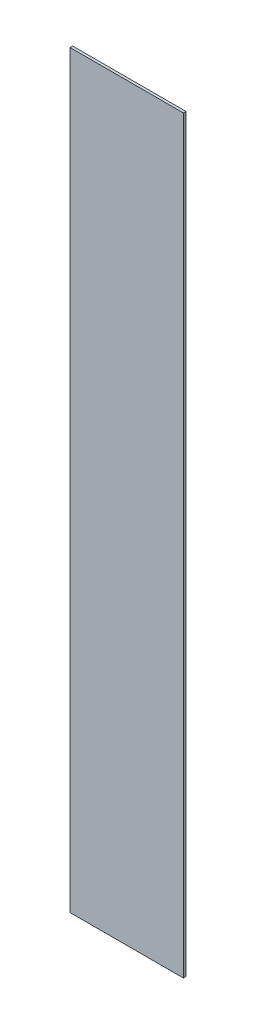
SolidWorks part; units mm, degrees
material "Chapa F.F 1020 - 1,5 mm"
ref_plane "Plano frontal" through (0, 0, 0) normal (0, 0, 1) x (1, 0, 0)
ref_plane "Plano superior" through (0, 0, 0) normal (0, 1, 0) x (1, 0, 0)
ref_plane "Plano direito" through (0, 0, 0) normal (1, 0, 0) x (0, 0, -1)
sketch "Esboço1" plane through (0, 0, 0) normal (0, 0, 1) x (1, 0, 0)
  line L1 (0, 0) -> (65, 0)
  line L2 (0, 0) -> (0, 430)
  line L3 (0, 430) -> (65, 430)
  line L4 (65, 0) -> (65, 430)
  dimension "D1" = 430
  dimension "D2" = 65
extrude "Ressalto-extrusão1" add sketch "Esboço1" along normal blind 1.5
